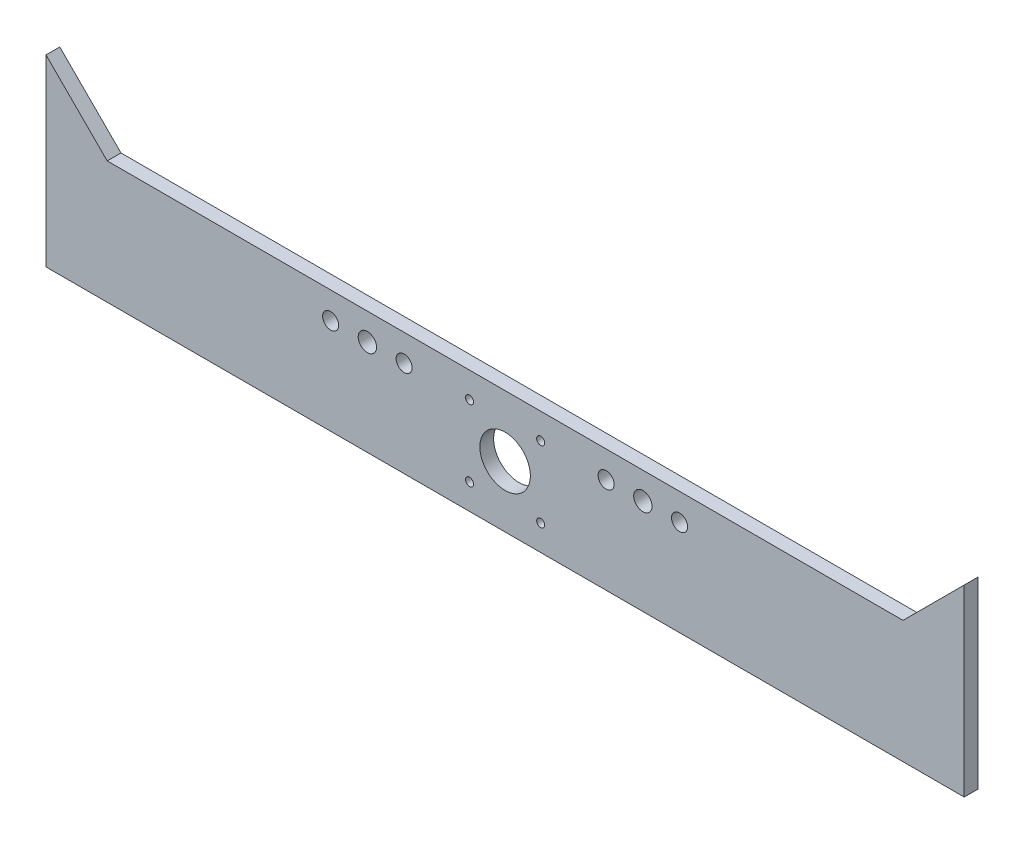
SolidWorks part; units mm, degrees
ref_plane "Front Plane" through (0, 0, 0) normal (0, 0, 1) x (1, 0, 0)
ref_plane "Top Plane" through (0, 0, 0) normal (0, 1, 0) x (1, 0, 0)
ref_plane "Right Plane" through (0, 0, 0) normal (1, 0, 0) x (0, 0, -1)
sketch "Sketch1" plane through (0, 0, 0) normal (0, 0, 1) x (1, 0, 0)
  line L0 (0, -1000) -> (0, 49000) construction
  line L1 (-1000, 0) -> (49000, 0) construction
  line L2 (-1173.1632, 53.3333) -> (48826.8368, 53.3333) construction
  line L3 (-200, 0) -> (200, 0)
  line L4 (-200, 0) -> (-200, 80)
  line L6 (200, 0) -> (200, 80)
  line L7 (200, 80) -> (173.3333, 53.3333)
  line L8 (-200, 80) -> (-173.3333, 53.3333)
  line L9 (-173.3333, 53.3333) -> (173.3333, 53.3333)
  point P9 (0, 0)
  dimension "D1" = 26.6667
  dimension "D2" = 400
  dimension "D3" = 80
  dimension "D5" = 45
extrude "Boss-Extrude1" add sketch "Sketch1" along normal blind 6
sketch "Sketch2" plane through (0, 0, 6) normal (0, 0, 1) x (1, 0, 0)
  line L0 (0, -1000) -> (0, 49000) construction
  line L1 (-1200, 26.665) -> (48800, 26.665) construction
  line L4 (-200, 0) -> (200, 0) construction
  line L5 (44, 41.665) -> (76, 41.665) construction
  circle A0 centre (0, 26.665) radius 11
  circle A1 centre (15.5, 42.165) radius 1.75
  circle A2 centre (-15.5, 42.165) radius 1.75
  circle A3 centre (-15.5, 11.165) radius 1.75
  circle A4 centre (15.5, 11.165) radius 1.75
  circle A5 centre (60, 41.665) radius 4
  circle A6 centre (76, 41.665) radius 3.5
  circle A7 centre (44, 41.665) radius 3.5
  circle A8 centre (-44, 41.665) radius 3.5
  circle A9 centre (-76, 41.665) radius 3.5
  circle A10 centre (-60, 41.665) radius 4
  point P22 (60, 41.665)
  dimension "D1" = 22
  dimension "D5" = 3.5
  dimension "D8" = 8
  dimension "D10" = 7
  dimension "D11" = 7
  dimension "D2" = 26.665
  dimension "D3" = 15.5
  dimension "D4" = 15.5
  dimension "D6" = 15
  dimension "D7" = 60
  dimension "D9" = 32
extrude "Cut-Extrude1" cut sketch "Sketch2" against normal through all
